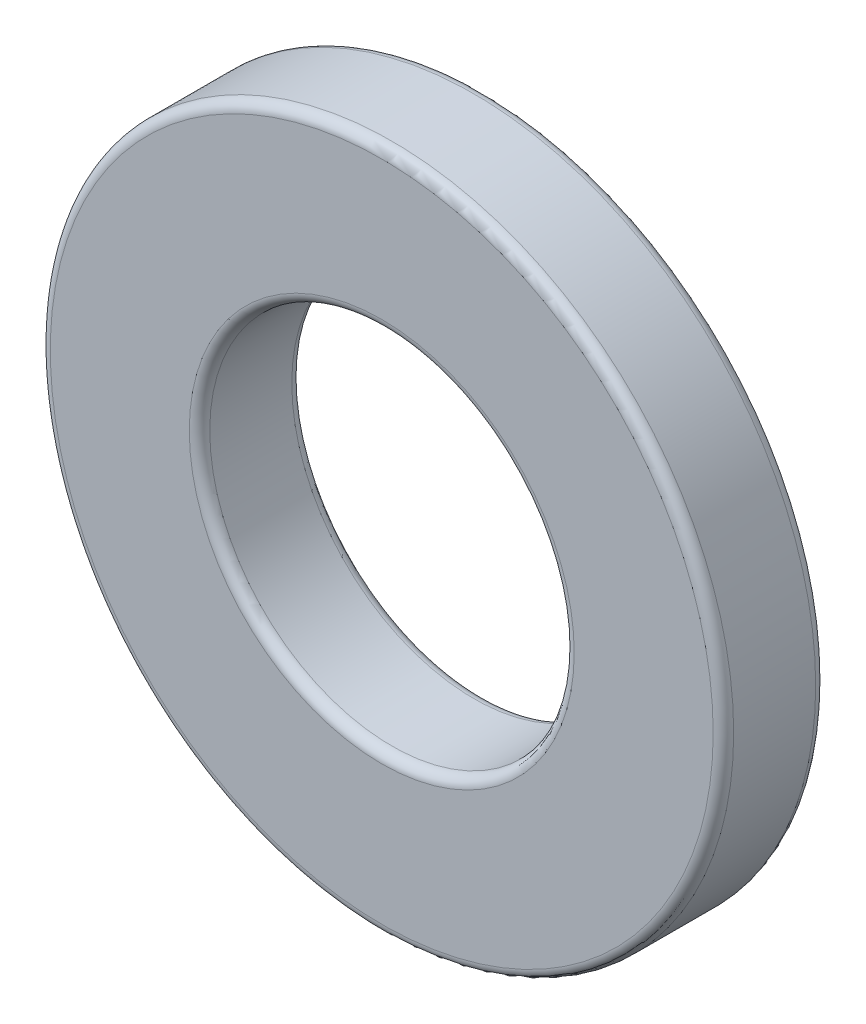
SolidWorks part; units mm, degrees
ref_plane "Front Plane" through (0, 0, 0) normal (0, 0, 1) x (1, 0, 0)
ref_plane "Top Plane" through (0, 0, 0) normal (0, 1, 0) x (1, 0, 0)
ref_plane "Right Plane" through (0, 0, 0) normal (1, 0, 0) x (0, 0, -1)
sketch "Sketch1" plane through (0, 0, 0) normal (0, 0, 1) x (1, 0, 0)
  circle A0 centre (0, 0) radius 6 construction
  circle A1 centre (0, 0) radius 3.2 construction
  dimension "OD" = 12
  dimension "ID" = 6.4
sketch "Sketch2" plane through (0, 0, 0) normal (1, 0, 0) x (0, 0, -1)
  line L0 (-0.9, -6) -> (0.9, -6) construction
  point P0 (0.5, -6)
  point P4 (0, -6)
  dimension "Thickness Max" = 1.8
  dimension "Thickness Min" = 1.4
sketch "Sketch3" plane through (0, 0, 0) normal (0, 0, 1) x (1, 0, 0)
  circle A0 centre (0, 0) radius 6 construction
  circle A1 centre (0, 0) radius 6
  circle A2 centre (0, 0) radius 3.2 construction
  circle A3 centre (0, 0) radius 3.2
extrude "Boss-Extrude1" add sketch "Sketch3" against normal up to vertex (0.9 mm away) and the other way up to vertex (0.9 mm away) up to point (0, -6, -0.9) other way up to point (0, -6, 0.9)
fillet "Fillet1" radius 0.18 4 edges at (6, 0, -0.9) (3.2, 0, -0.9) (3.2, 0, 0.9) (6, 0, 0.9)
equation "\"D1@Fillet1\" = \"Thickness Max@Sketch2\" * 0.1"
